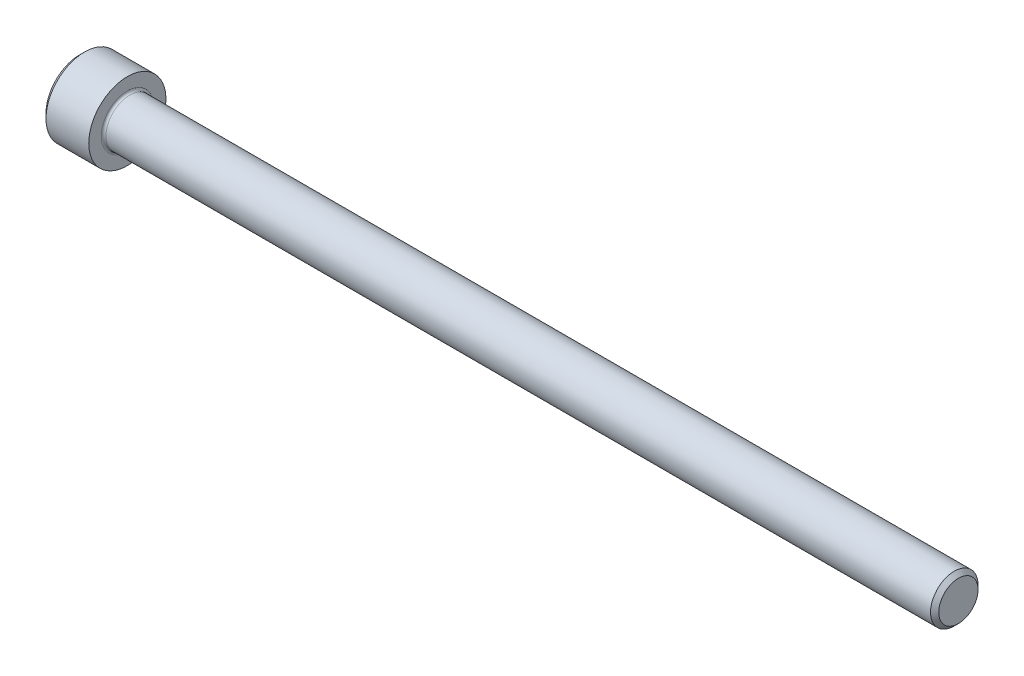
SolidWorks part; units mm, degrees
revolve "Base-Revolve" add sketch "BodySke"
sketch "BodySke" plane through (0, 0, 0) normal (0, 0, 1) x (1, 0, 0)
  line L0 (0, 0) -> (0, 5.7)
  line L1 (0.8, 6.5) -> (8, 6.5)
  line L2 (8, 6.5) -> (8, 4)
  line L3 (8, 4) -> (147.3095, 4)
  line L4 (148, 3.3095) -> (148, 0)
  line L5 (148, 0) -> (0, 0)
  line L6 (-31.75, 0) -> (127, 0) construction
  line L7 (0, 5.7) -> (0.8, 6.5)
  line L8 (148, 3.3095) -> (147.3095, 4)
  line L9 (0, -5.7) -> (0.8, -6.5) construction
  line L10 (148, -3.3095) -> (147.3095, -4) construction
  line L11 (9.25, 2.4825) -> (9.25, -3.8675) construction
  line L12 (120, 2.4825) -> (120, -3.8675) construction
  line L13 (98, 2.4825) -> (98, -3.8675) construction
  dimension "Diameter" = 8
  dimension "Head_ht" = 8
  dimension "Length" = 140
  dimension "Body_ch_ang" = 45
  dimension "Head_dia" = 13
  dimension "Head_ch_ang" = 45
  dimension "Minor_dia" = 6.619
  dimension "Advance" = 1.25
  dimension "Thread_nom" = 28
  dimension "Thread_length" = 50
  dimension "Head_ch_ht" = 0.8
cosmetic thread "ThreadCosmetic" [suppressed]
fillet "Fillet1" radius 0.4 1 edges at (8, 0, 4)
ref_plane "Plane1" through (0, 0, 0) normal (0, 0, 1) x (1, 0, 0)
ref_plane "Plane2" through (0, 0, 0) normal (0, 1, 0) x (1, 0, 0)
ref_plane "Plane3" through (0, 0, 0) normal (1, 0, 0) x (0, 0, -1)
other "Configuration Table"
sketch "Sketch2" plane through (0, 0, 0) normal (0, 0, 1) x (1, 0, 0)
  line L0 (0, 3.0475) -> (4, 3.0475)
  line L1 (4, 3.0475) -> (5.7595, 0)
  line L2 (-31.75, 0) -> (127, 0) construction
  line L3 (5.7595, 0) -> (0, 0)
  line L4 (0, 0) -> (0, 3.0475)
  line L5 (0, 5.7) -> (0, -5.7) construction
  line L6 (0, 0) -> (47.625, 0) construction
  line L7 (8, -6.5) -> (8, 6.5) construction
  dimension "D1" = 3.0475
  dimension "D2" = 60
revolve "Hex-PreBroach" cut sketch "Sketch2" angle 360 about L6
sketch "Sketch3" plane through (0, 0, 0) normal (-1, 0, 0) x (0, 0.5, 0.866)
  line L0 (1.7595, 3.0475) -> (-1.7595, 3.0475)
  line L1 (-1.7595, 3.0475) -> (-3.5189, 0)
  line L2 (1.7595, 3.0475) -> (3.5189, 0)
  line L3 (1.7595, -3.0475) -> (3.5189, 0)
  line L4 (1.7595, -3.0475) -> (-1.7595, -3.0475)
  line L5 (-1.7595, -3.0475) -> (-3.5189, 0)
  dimension "D1" = 3.0475
  dimension "D2" = 3.0475
  dimension "Hex_size" = 6.095
extrude "Hex" cut sketch "Sketch3" against normal blind 4
sketch "Sketch4" plane through (0, 0, 0) normal (-1, 0, 0) x (0, 0, 1)
  line L0 (0, 0) -> (3.7846, 0)
  line L1 (0, 0) -> (6.1484, 3.5498) construction
  line L2 (0, 0) -> (1.8923, 3.2776)
  line L3 (3.1235, 0.8061) -> (3.6229, 1.0945)
  line L4 (2.2599, 2.3019) -> (2.7593, 2.5903)
  arc A0 (3.1235, 0.8061) -> (2.2599, 2.3019) centre (0, 0) ccw
  arc A1 (3.7846, 0) -> (3.6229, 1.0945) centre (0, 0) ccw
  arc A2 (1.8923, 3.2776) -> (2.7593, 2.5903) centre (0, 0) cw
  dimension "D1" = 30
  dimension "D2" = 60
  dimension "Spline_p_dim" = 1.7272
  dimension "D3" = 0.8636
extrude "Spline" [suppressed] cut sketch "Sketch4" against normal blind 4
pattern_circular "CirPattern1" [suppressed] count 6 every 60
sketch "Sketch5" plane through (0, 0, 0) normal (0, 0, 1) x (1, 0, 0)
  line L0 (-31.75, 0) -> (127, 0) construction
  line L2 (0, 5.7) -> (0, -5.7) construction
  circle A0 centre (2.7, 0) radius 0.675
  dimension "Drilled_hole_dia" = 1.35
  dimension "Drilled_hole_loc" = 2.7
extrude "Hole" [suppressed] cut sketch "Sketch5" against normal through all and the other way through all
pattern_circular "Drilled-4" [suppressed] count 2 every 60
pattern_circular "Drilled-6" [suppressed] count 3 every 60
sketch "ThdSchSke" plane through (0, 0, 0) normal (0, 0, 1) x (1, 0, 0)
  line L0 (120, -3.3095) -> (119.5165, -4)
  line L1 (120, -3.3095) -> (120.4835, -4)
  line L2 (120.4835, -4) -> (120.4835, -5)
  line L3 (-3.175, 0) -> (5.1513, 0) construction
  line L5 (120.4835, -5) -> (119.5165, -5)
  line L6 (119.5165, -5) -> (119.5165, -4)
  line L7 (0, 5.7) -> (0, -5.7) construction
  dimension "Thread_minor" = 6.619
  dimension "Diameter" = 8
  dimension "Start" = 120
revolve "ThreadSchematic" [suppressed] cut sketch "ThdSchSke" angle 360 about L3
pattern_linear "ThdSchPat" [suppressed]
equation "\"D2@Sketch3\" = \"Hex_size@Sketch3\" / 2"
equation "\"D1@Sketch3\" = \"Hex_size@Sketch3\" / 2"
equation "\"D1@Sketch2\" = \"Hex_size@Sketch3\" / 2"
equation "\"D3@Sketch4\" = \"Spline_p_dim@Sketch4\" / 2"
equation "\"Thread_minor@ThreadCosmetic\"  =  \"Minor_dia@BodySke\""
equation "\"D2@CirPattern1\" = 360 / \"Num_teeth@CirPattern1\""
equation "\"Wall_thickness@Sketch2\" = \"Head_ht@BodySke\" - \"Key_eng@Hex\""
equation "\"Thread_length@ThreadCosmetic\" = ((sgn( (\"Length@BodySke\" - \"Advance@BodySke\" ) - \"Thread_nom@BodySke\" )-1)*( (\"Length@BodySke\" - \"Advance@BodySke\" ) - \"Thread_nom@BodySke\" ))/-2+ \"Thread_nom@BodySke\""
equation "\"Thread_minor@ThdSchSke\" = \"Minor_dia@BodySke\""
equation "\"Diameter@ThdSchSke\" = \"Diameter@BodySke\""
equation "\"Overcut@ThdSchSke\" = \"Diameter@BodySke\" * 1.25"
equation "\"Start@ThdSchSke\" = \"Head_ht@BodySke\" + \"Length@BodySke\" - \"Thread_length@ThreadCosmetic\"  '---Non-countersunk---"
equation "\"Num_threads@ThdSchPat\" = int( \"Thread_length@ThreadCosmetic\" / \"Advance@BodySke\" + 0.999 )  + 1"
equation "\"Advance@ThdSchPat\" = \"Thread_length@ThreadCosmetic\" /  (\"Num_threads@ThdSchPat\" - 1) 'relax it"
equation "\"Num_threads@ThdSchPat\" = \"Num_threads@ThdSchPat\" - sgn( \"Num_threads@ThdSchPat\" - 1) '---chamfered tips only---"
